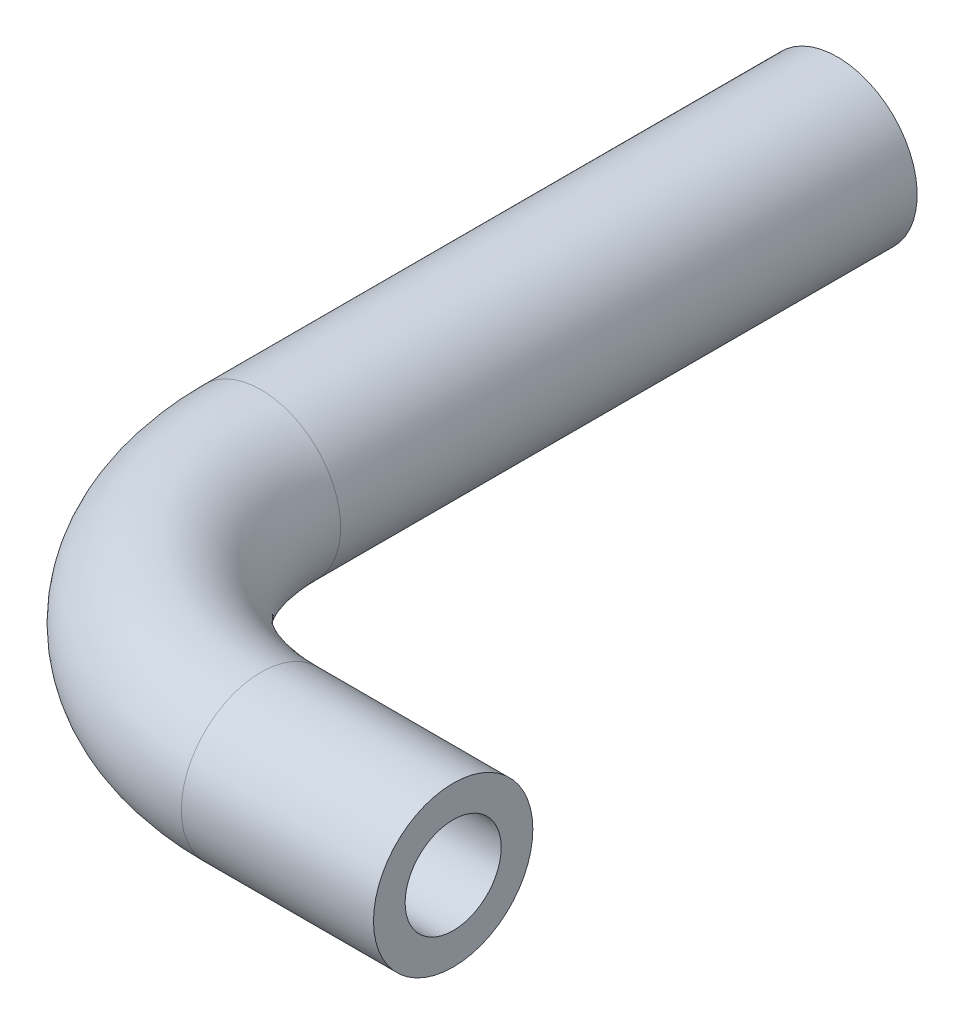
SolidWorks part; units mm, degrees
material "NEOPRENE"
ref_plane "Front" through (0, 0, 0) normal (0, 0, 1) x (1, 0, 0)
ref_plane "Top" through (0, 0, 0) normal (0, 1, 0) x (1, 0, 0)
ref_plane "Right" through (0, 0, 0) normal (1, 0, 0) x (0, 0, -1)
sketch "Sketch1" plane through (0, 0, 0) normal (0, 1, 0) x (1, 0, 0)
  arc A0 (0, 0) -> (-32.3403, 32.3403) centre (0, 32.3403) cw
  point P3 (-36.9613, 34.3034)
  point P5 (0, 0)
  point P6 (-32.3351, 31.7586)
  point P7 (0, 0)
  point P8 (0, 0)
  dimension "D1" = 32.3403
sketch "Sketch2" plane through (0, 0, 0) normal (1, 0, 0) x (0, 0, -1)
  circle A0 centre (0, 0) radius 6.35
  circle A1 centre (0, 0) radius 10.5309
  dimension "D1" = 21.0618
  dimension "D2" = 12.7
sweep "Sweep1" add profiles "Sketch2" path "Sketch1"
sketch "Sketch3" plane through (0, 0, -32.3403) normal (0, 0, -1) x (-1, 0, 0)
  circle A0 centre (32.3403, 0) radius 6.35 construction
  circle A1 centre (32.3403, 0) radius 10.5309 construction
  circle A2 centre (32.3403, 0) radius 6.35
  circle A3 centre (32.3403, 0) radius 10.5309
extrude "Boss-Extrude1" add sketch "Sketch3" along normal blind 76.2
sketch "Sketch4" plane through (0, 0, 0) normal (1, 0, 0) x (0, 0, -1)
  circle A0 centre (0, 0) radius 6.35 construction
  circle A1 centre (0, 0) radius 10.5309
  circle A2 centre (0, 0) radius 10.5309
  circle A3 centre (0, 0) radius 6.35
  dimension "D1" = 0
extrude "Boss-Extrude2" add sketch "Sketch4" along normal blind 25.4
